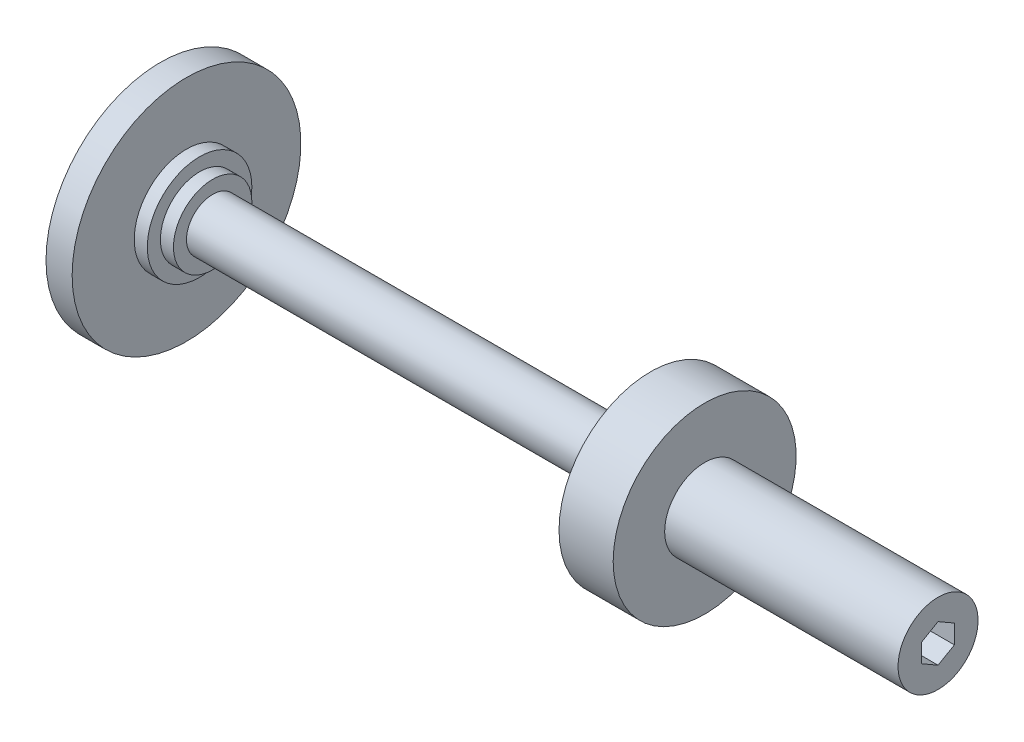
SolidWorks part; units mm, degrees
ref_plane "Front Plane" through (0, 0, 0) normal (0, 0, 1) x (1, 0, 0)
ref_plane "Top Plane" through (0, 0, 0) normal (0, 1, 0) x (1, 0, 0)
ref_plane "Right Plane" through (0, 0, 0) normal (1, 0, 0) x (0, 0, -1)
sketch "Sketch1" plane through (0, 0, 0) normal (0, 0, 1) x (1, 0, 0)
  line L0 (0, 0) -> (139.7, 0) construction
  line L1 (139.7, 0) -> (139.7, 19.4437)
  line L2 (139.7, 19.4437) -> (26.3144, 19.4437)
  line L3 (26.3144, 19.4437) -> (26.3144, 44.45)
  line L4 (26.3144, 44.45) -> (0, 44.45)
  line L5 (0, 44.45) -> (0, 0)
  line L6 (0, 0) -> (139.7, 0)
  dimension "D1" = 88.9
  dimension "D2" = 38.8874
  dimension "D3" = 26.3144
  dimension "D4" = 113.3856
revolve "Revolve_Chuck" add sketch "Sketch1" angle 360 about L0
sketch "Sketch2" plane through (0, 0, 0) normal (-1, 0, 0) x (0, 0, 1)
  circle A0 centre (0, 0) radius 12.7
  dimension "D1" = 25.4
extrude "Boss-Extrude1" add sketch "Sketch2" along normal blind 254
sketch "Sketch4" plane through (-254, 0, 0) normal (-1, 0, 0) x (0, 0, 1)
  circle A0 centre (0, 0) radius 55.5625
  circle A1 centre (0, 0) radius 12.7 construction
  circle A2 centre (0, 0) radius 12.7
  dimension "D1" = 111.125
extrude "Boss-Extrude2" add sketch "Sketch4" against normal blind 12.7 from offset 15.875 separate body offset against normal yes
sketch "Sketch5" plane through (139.7, 0, 0) normal (1, 0, 0) x (0, 0, -1)
  line L1 (0, 9.1654) -> (-7.9375, 4.5827)
  line L2 (-7.9375, 4.5827) -> (-7.9375, -4.5827)
  line L3 (-7.9375, -4.5827) -> (0, -9.1654)
  line L4 (0, -9.1654) -> (7.9375, -4.5827)
  line L5 (7.9375, -4.5827) -> (7.9375, 4.5827)
  line L6 (7.9375, 4.5827) -> (0, 9.1654)
  circle A0 centre (0, 0) radius 7.9375 construction
  dimension "D1" = 15.875
extrude "Cut-Extrude1" cut sketch "Sketch5" against normal blind 63.5
sketch "Sketch6" plane through (0, 0, 0) normal (0, 0, 1) x (1, 0, 0)
  line L0 (-238.125, 12.7) -> (-238.125, 25.4)
  line L1 (-238.125, 55.5625) -> (-238.125, -55.5625) construction
  line L2 (-238.125, 25.4) -> (-244.475, 25.4)
  line L3 (-244.475, 25.4) -> (-244.475, 19.05)
  line L4 (-244.475, 19.05) -> (-250.825, 19.05)
  line L5 (-250.825, 19.05) -> (-250.825, 12.7)
  line L6 (-250.825, 12.7) -> (-238.125, 12.7)
  line L7 (0, 12.7) -> (-254, 12.7) construction
  line L8 (-254, 12.7) -> (-254, -12.7) construction
  line L9 (-254, 0) -> (-447.2083, 0) construction
  line L10 (-231.775, 55.5625) -> (-231.775, -55.5625) construction
  line L11 (-225.425, 55.5625) -> (-238.125, 55.5625) construction
  line L12 (-238.125, -55.5625) -> (-225.425, -55.5625) construction
  line L13 (-212.725, 12.7) -> (-225.425, 12.7)
  line L14 (-212.725, 19.05) -> (-212.725, 12.7)
  line L15 (-219.075, 19.05) -> (-212.725, 19.05)
  line L16 (-219.075, 25.4) -> (-219.075, 19.05)
  line L17 (-225.425, 25.4) -> (-219.075, 25.4)
  line L18 (-225.425, 12.7) -> (-225.425, 25.4)
  dimension "D1" = 3.175
  dimension "D2" = 6.35
  dimension "D3" = 12.7
  dimension "D4" = 38.1
  dimension "D5" = 50.8
revolve "Revolve1" add sketch "Sketch6" angle 360 about L9
